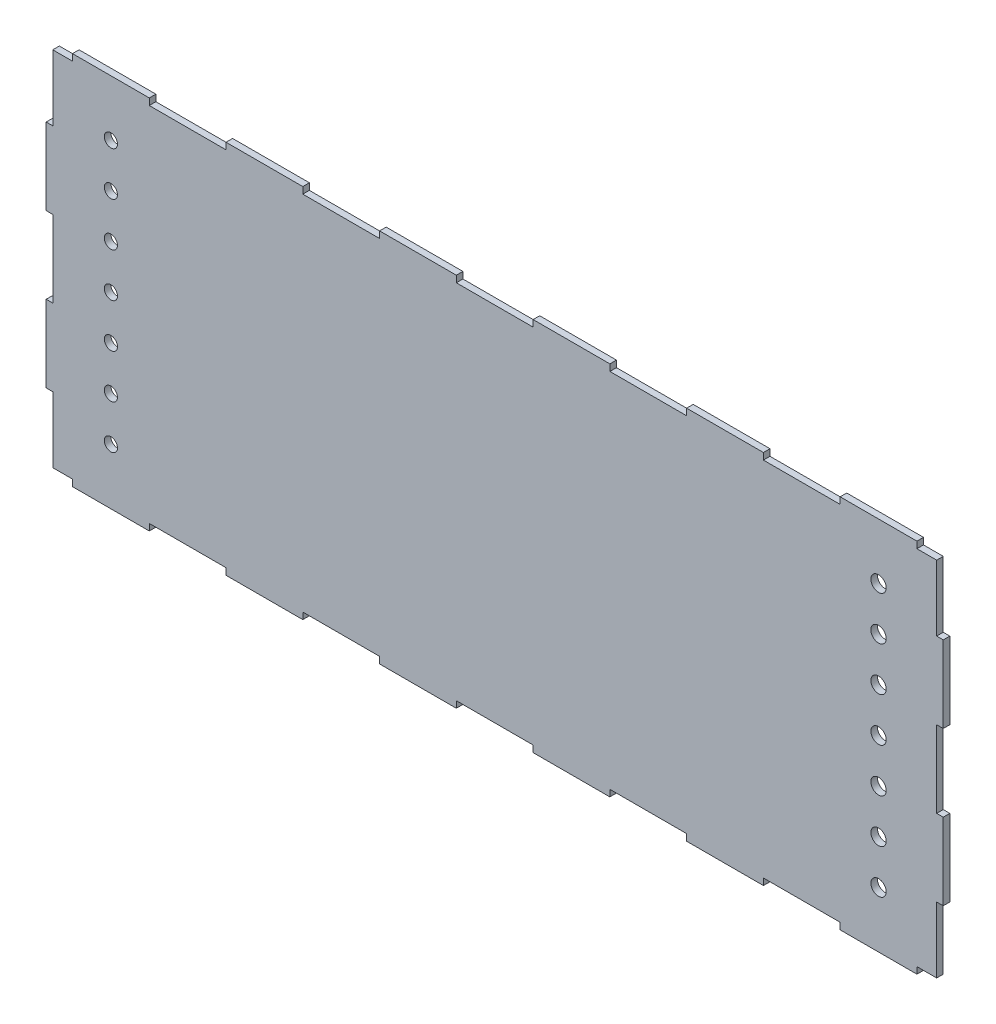
SolidWorks part; units mm, degrees
ref_plane "Front Plane" through (0, 0, 0) normal (0, 0, 1) x (1, 0, 0)
ref_plane "Top Plane" through (0, 0, 0) normal (0, 1, 0) x (1, 0, 0)
ref_plane "Right Plane" through (0, 0, 0) normal (1, 0, 0) x (0, 0, -1)
sketch "Model" plane through (0, 0, 0) normal (0, 0, 1) x (1, 0, 0)
  line L0 (192.5, 85.5) -> (157.5, 85.5)
  line L1 (157.5, 85.5) -> (157.5, 82.5)
  line L2 (157.5, 82.5) -> (122.5, 82.5)
  line L3 (122.5, 82.5) -> (122.5, 85.5)
  line L4 (122.5, 85.5) -> (87.5, 85.5)
  line L5 (87.5, 85.5) -> (87.5, 82.5)
  line L6 (87.5, 82.5) -> (52.5, 82.5)
  line L7 (52.5, 82.5) -> (52.5, 85.5)
  line L8 (52.5, 85.5) -> (17.5, 85.5)
  line L9 (17.5, 85.5) -> (17.5, 82.5)
  line L10 (17.5, 82.5) -> (-17.5, 82.5)
  line L11 (-17.5, 82.5) -> (-17.5, 85.5)
  line L12 (-17.5, 85.5) -> (-52.5, 85.5)
  line L13 (-52.5, 85.5) -> (-52.5, 82.5)
  line L14 (-52.5, 82.5) -> (-87.5, 82.5)
  line L15 (-87.5, 82.5) -> (-87.5, 85.5)
  line L16 (-87.5, 85.5) -> (-122.5, 85.5)
  line L17 (-122.5, 85.5) -> (-122.5, 82.5)
  line L18 (-122.5, 82.5) -> (-157.5, 82.5)
  line L19 (-157.5, 82.5) -> (-157.5, 85.5)
  line L20 (-157.5, 85.5) -> (-192.5, 85.5)
  line L21 (-192.5, 85.5) -> (-192.5, 82.5)
  line L22 (-192.5, 82.5) -> (-201.5, 82.5)
  line L23 (-201.5, 82.5) -> (-201.5, 52.5)
  line L24 (-201.5, 52.5) -> (-204.5, 52.5)
  line L25 (-204.5, 52.5) -> (-204.5, 17.5)
  line L26 (-204.5, 17.5) -> (-201.5, 17.5)
  line L27 (-201.5, 17.5) -> (-201.5, -17.5)
  line L28 (-201.5, -17.5) -> (-204.5, -17.5)
  line L29 (-204.5, -17.5) -> (-204.5, -52.5)
  line L30 (-204.5, -52.5) -> (-201.5, -52.5)
  line L31 (-201.5, -52.5) -> (-201.5, -82.5)
  line L32 (-201.5, -82.5) -> (-192.5, -82.5)
  line L33 (-192.5, -82.5) -> (-192.5, -85.5)
  line L34 (-192.5, -85.5) -> (-157.5, -85.5)
  line L35 (-157.5, -85.5) -> (-157.5, -82.5)
  line L36 (-157.5, -82.5) -> (-122.5, -82.5)
  line L37 (-122.5, -82.5) -> (-122.5, -85.5)
  line L38 (-122.5, -85.5) -> (-87.5, -85.5)
  line L39 (-87.5, -85.5) -> (-87.5, -82.5)
  line L40 (-87.5, -82.5) -> (-52.5, -82.5)
  line L41 (-52.5, -82.5) -> (-52.5, -85.5)
  line L42 (-52.5, -85.5) -> (-17.5, -85.5)
  line L43 (-17.5, -85.5) -> (-17.5, -82.5)
  line L44 (-17.5, -82.5) -> (17.5, -82.5)
  line L45 (17.5, -82.5) -> (17.5, -85.5)
  line L46 (17.5, -85.5) -> (52.5, -85.5)
  line L47 (52.5, -85.5) -> (52.5, -82.5)
  line L48 (52.5, -82.5) -> (87.5, -82.5)
  line L49 (87.5, -82.5) -> (87.5, -85.5)
  line L50 (87.5, -85.5) -> (122.5, -85.5)
  line L51 (122.5, -85.5) -> (122.5, -82.5)
  line L52 (122.5, -82.5) -> (157.5, -82.5)
  line L53 (157.5, -82.5) -> (157.5, -85.5)
  line L54 (157.5, -85.5) -> (192.5, -85.5)
  line L55 (192.5, -85.5) -> (192.5, -82.5)
  line L56 (192.5, -82.5) -> (201.5, -82.5)
  line L57 (201.5, -82.5) -> (201.5, -52.5)
  line L58 (201.5, -52.5) -> (204.5, -52.5)
  line L59 (204.5, -52.5) -> (204.5, -17.5)
  line L60 (204.5, -17.5) -> (201.5, -17.5)
  line L61 (201.5, -17.5) -> (201.5, 17.5)
  line L62 (201.5, 17.5) -> (204.5, 17.5)
  line L63 (204.5, 17.5) -> (204.5, 52.5)
  line L64 (204.5, 52.5) -> (201.5, 52.5)
  line L65 (201.5, 52.5) -> (201.5, 82.5)
  line L66 (201.5, 82.5) -> (192.5, 82.5)
  line L67 (192.5, 82.5) -> (192.5, 85.5)
extrude "Boss-Extrude1" add sketch "Model" along normal blind 3
sketch "Sketch1" plane through (0, 0, 3) normal (0, 0, 1) x (1, 0, 0)
  line L0 (0, 0) -> (0, 86) construction
  line L1 (0, 86) -> (175, 86) construction
  line L2 (0, 86) -> (-175, 86) construction
  line L3 (-175, 86) -> (-175, -86) construction
  line L4 (-175, -86) -> (175, -86) construction
  line L5 (175, -86) -> (175, 86) construction
  circle A0 centre (-175, 0) radius 3
  circle A1 centre (175, 0) radius 3.5
  circle A2 centre (-175, 20) radius 3
  circle A3 centre (175, 20) radius 3.5
  circle A4 centre (-175, 40) radius 3
  circle A5 centre (175, 40) radius 3.5
  circle A6 centre (-175, 60) radius 3
  circle A7 centre (175, 60) radius 3.5
  circle A8 centre (-175, -20) radius 3
  circle A9 centre (175, -20) radius 3.5
  circle A10 centre (-175, -40) radius 3
  circle A11 centre (175, -40) radius 3.5
  circle A12 centre (-175, -60) radius 3
  circle A13 centre (175, -60) radius 3.5
  dimension "D3" = 6
  dimension "D4" = 7
  dimension "D1" = 175
  dimension "D2" = 175
extrude "Cut-Extrude1" cut sketch "Sketch1" against normal through all
